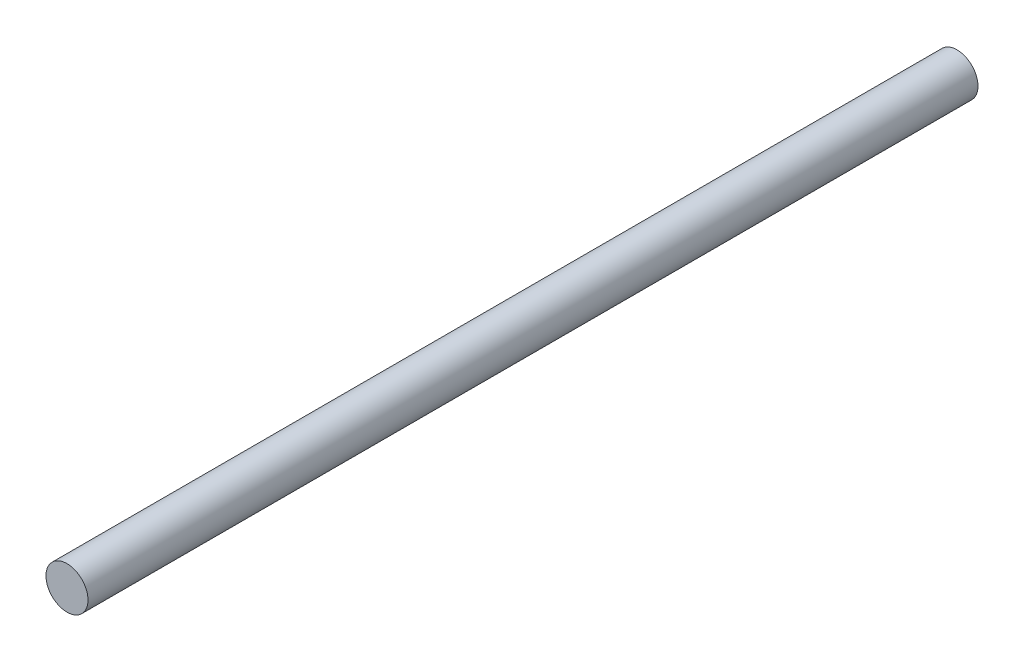
SolidWorks part; units mm, degrees
material "Plain Carbon Steel"
ref_plane "Front Plane" through (0, 0, 0) normal (0, 0, 1) x (1, 0, 0)
ref_plane "Top Plane" through (0, 0, 0) normal (0, 1, 0) x (1, 0, 0)
ref_plane "Right Plane" through (0, 0, 0) normal (1, 0, 0) x (0, 0, -1)
sketch "Sketch1" plane through (0, 0, 0) normal (0, 0, 1) x (1, 0, 0)
  circle A0 centre (0, 0) radius 3
  dimension "D1" = 6
extrude "Boss-Extrude1" add sketch "Sketch1" along normal blind 127
